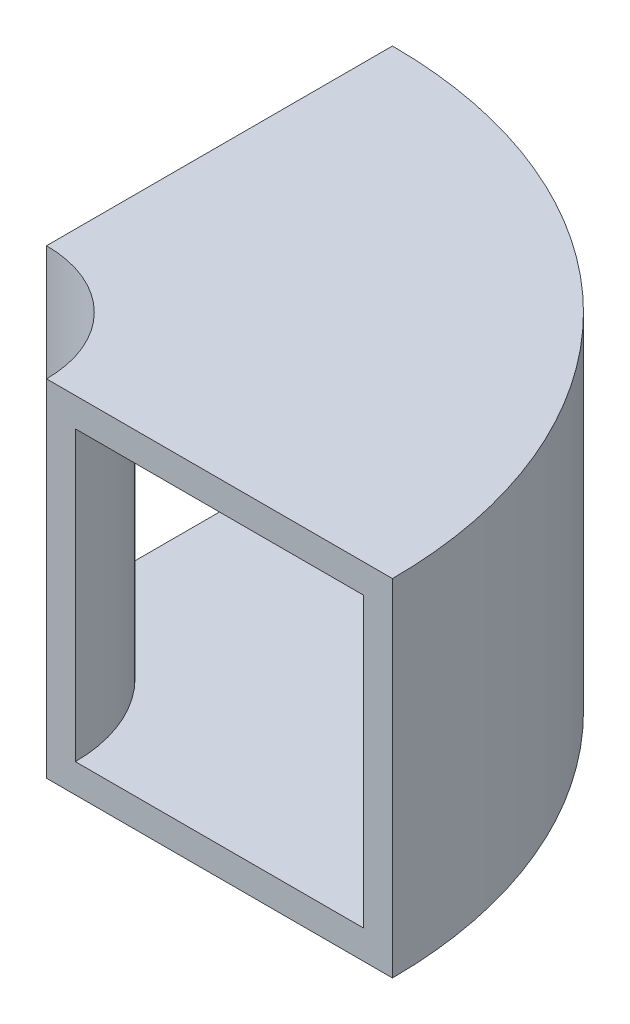
SolidWorks part; units mm, degrees
ref_plane "前视基准面" through (0, 0, 0) normal (0, 0, 1) x (1, 0, 0)
ref_plane "上视基准面" through (0, 0, 0) normal (0, 1, 0) x (1, 0, 0)
ref_plane "右视基准面" through (0, 0, 0) normal (1, 0, 0) x (0, 0, -1)
other "Configuration Table"
sketch "草图1" plane through (0, 0, 0) normal (0, 0, 1) x (1, 0, 0)
  line L0 (0, 0) -> (0, 20) construction
  line L2 (5, 0) -> (15, 0)
  line L3 (5, 0) -> (5, 10)
  line L4 (5, 10) -> (15, 10)
  line L5 (15, 0) -> (15, 10)
revolve "ThinRevolve90" add sketch "草图1" angle 90 about L0
